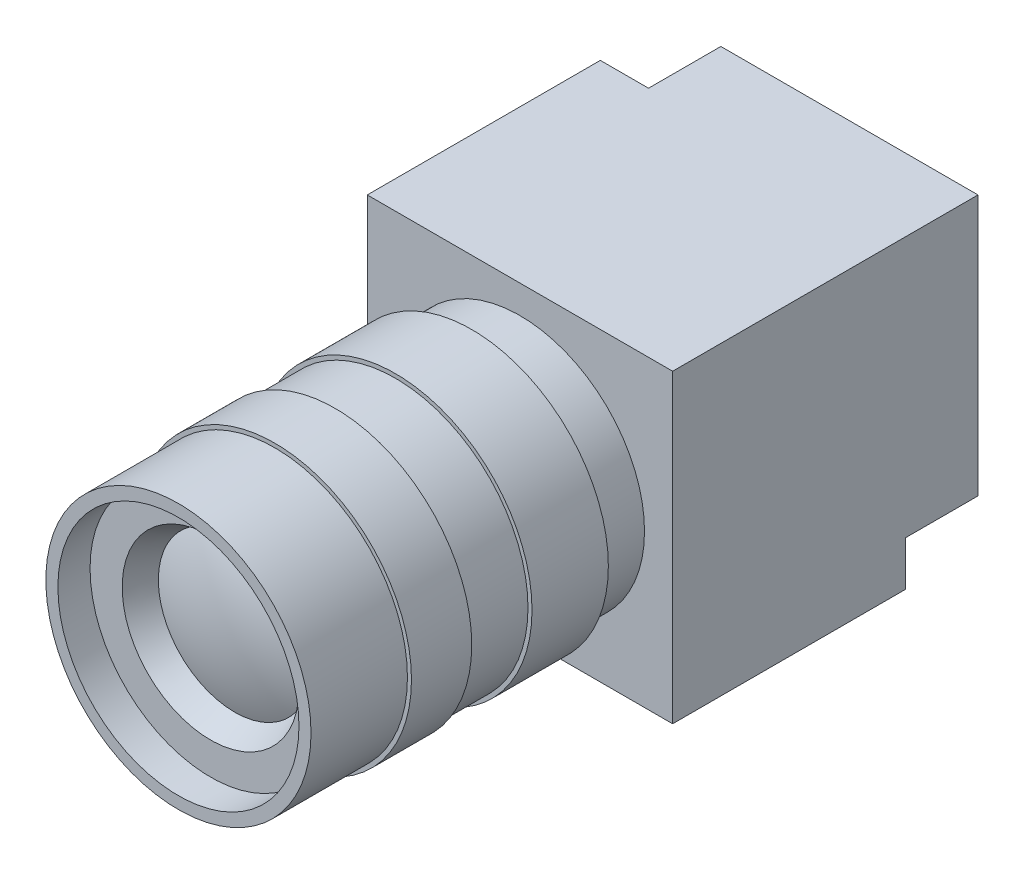
SolidWorks part; units mm, degrees
ref_plane "前视基准面" through (0, 0, 0) normal (0, 0, 1) x (1, 0, 0)
ref_plane "上视基准面" through (0, 0, 0) normal (0, 1, 0) x (1, 0, 0)
ref_plane "右视基准面" through (0, 0, 0) normal (1, 0, 0) x (0, 0, -1)
sketch "草图1" plane through (0, 0, 0) normal (0, 0, 1) x (1, 0, 0)
  line L1 (-19, 19) -> (19, 19)
  line L2 (-19, 19) -> (-19, -19)
  line L3 (-19, -19) -> (19, -19)
  line L4 (19, 19) -> (19, -19)
  dimension "D1" = 19
  dimension "D2" = 38
  dimension "D3" = 38
  dimension "D4" = 19
extrude "拉伸1" add sketch "草图1" along normal blind 38
sketch "草图2" plane through (0, 0, 38) normal (0, 0, 1) x (1, 0, 0)
  circle A0 centre (0, 0) radius 15.5
  dimension "D1" = 31
extrude "拉伸2" add sketch "草图2" along normal blind 6
sketch "草图3" plane through (0, 0, 44) normal (0, 0, 1) x (1, 0, 0)
  circle A0 centre (0, 0) radius 17
  dimension "D1" = 34
extrude "拉伸3" add sketch "草图3" along normal blind 9.5
sketch "草图4" plane through (0, 0, 53.5) normal (0, 0, 1) x (1, 0, 0)
  circle A0 centre (0, 0) radius 16.5
  dimension "D1" = 33
extrude "拉伸4" add sketch "草图4" along normal blind 7.5
sketch "草图5" plane through (0, 0, 61) normal (0, 0, 1) x (1, 0, 0)
  circle A0 centre (0, 0) radius 17
extrude "拉伸5" add sketch "草图5" along normal blind 7.5
sketch "草图6" plane through (0, 0, 68.5) normal (0, 0, 1) x (1, 0, 0)
  circle A0 centre (0, 0) radius 16.5
  dimension "D1" = 33
extrude "拉伸6" add sketch "草图6" along normal blind 12
sketch "草图8" plane through (0, 0, 0) normal (0, 1, 0) x (1, 0, 0)
  line L0 (0, -1080.5) -> (0, -75.3847) construction
  line L1 (-16.5, -80.5) -> (16.5, -80.5) construction
  line L2 (0, -80.5) -> (-15, -80.5)
  line L3 (-15, -80.5) -> (-15, -76.5)
  line L4 (-15, -76.5) -> (-11, -76.5)
  line L5 (-11, -76.5) -> (-9.5, -73.5)
  line L6 (0, -73.5) -> (0, 48919.5) construction
  line L7 (0, -75.3847) -> (0, -80.5)
  arc A0 (-9.5, -73.5) -> (0, -75.3847) centre (0, -50.5) ccw
  point P5 (0, -80.5)
  dimension "D1" = 15
  dimension "D2" = 9.5
  dimension "D3" = 7
  dimension "D4" = 4
  dimension "D5" = 4
  dimension "D6" = 30
revolve "切除-旋转1" cut sketch "草图8" angle 360 about L0
sketch "草图9" plane through (0, 0, 0) normal (0, 0, -1) x (-1, 0, 0)
  line L0 (-19, -19) -> (19, -19)
  line L1 (19, -19) -> (19, 19)
  line L2 (19, 19) -> (13, 19)
  line L3 (-19, 19) -> (19, 19) construction
  line L4 (13, 19) -> (13, -4)
  line L5 (13, -4) -> (-11, -4)
  line L6 (-11, -4) -> (-11, -13.44)
  line L7 (-11, -13.44) -> (-19, -13.44)
  line L8 (-19, -19) -> (-19, 19) construction
  line L9 (-19, -13.44) -> (-19, -19)
  dimension "D1" = 6
  dimension "D2" = 30
  dimension "D3" = 15
extrude "切除-拉伸1" cut sketch "草图9" against normal blind 9
